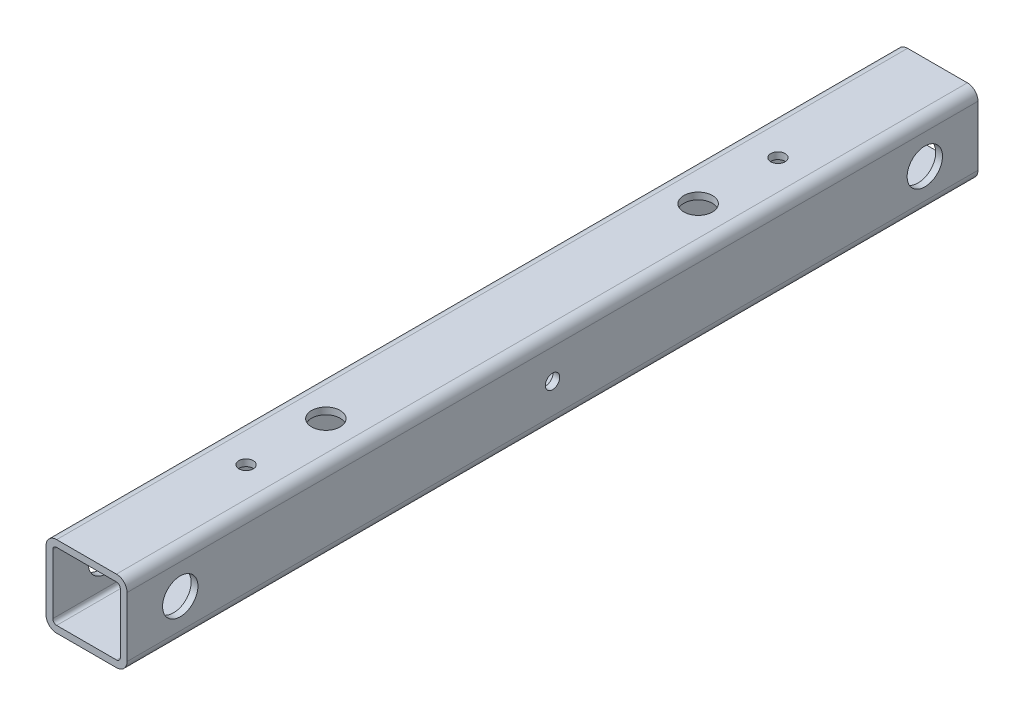
SolidWorks part; units mm, degrees
ref_plane "Front Plane" through (0, 0, 0) normal (0, 0, 1) x (1, 0, 0)
ref_plane "Top Plane" through (0, 0, 0) normal (0, 1, 0) x (1, 0, 0)
ref_plane "Right Plane" through (0, 0, 0) normal (1, 0, 0) x (0, 0, -1)
sketch "Sketch1" plane through (0, 0, 0) normal (0, 0, 1) x (1, 0, 0)
  line L6 (-14.05, 19.05) -> (14.05, 19.05)
  line L7 (19.05, 14.05) -> (19.05, -14.05)
  line L8 (-15.875, 14.05) -> (-15.875, -14.05)
  line L9 (-14.05, -15.875) -> (14.05, -15.875)
  line L10 (14.05, -19.05) -> (-14.05, -19.05)
  line L11 (-19.05, -14.05) -> (-19.05, 14.05)
  line L12 (0, 19.05) -> (0, -19.05) construction
  line L13 (-19.05, 0) -> (19.05, 0) construction
  line L14 (15.875, -14.05) -> (15.875, 14.05)
  line L15 (14.05, 15.875) -> (-14.05, 15.875)
  line L16 (0, 15.875) -> (0, -15.875) construction
  line L17 (-15.875, 0) -> (15.875, 0) construction
  arc A0 (14.05, 19.05) -> (19.05, 14.05) centre (14.05, 14.05) cw
  arc A1 (19.05, -14.05) -> (14.05, -19.05) centre (14.05, -14.05) cw
  arc A2 (-14.05, -19.05) -> (-19.05, -14.05) centre (-14.05, -14.05) cw
  arc A3 (-19.05, 14.05) -> (-14.05, 19.05) centre (-14.05, 14.05) cw
  arc A4 (-15.875, -14.05) -> (-14.05, -15.875) centre (-14.05, -14.05) ccw
  arc A5 (14.05, -15.875) -> (15.875, -14.05) centre (14.05, -14.05) ccw
  arc A6 (15.875, 14.05) -> (14.05, 15.875) centre (14.05, 14.05) ccw
  arc A7 (-14.05, 15.875) -> (-15.875, 14.05) centre (-14.05, 14.05) ccw
  point P40 (0, 0)
  dimension "D3" = 5
  dimension "D4" = 3.175
extrude "Boss-Extrude1" add sketch "Sketch1" along normal blind 400
sketch "Sketch2" plane through (0, 0, 0) normal (1, 0, 0) x (0, 0, -1)
  line L0 (-375, 0) -> (-25, 0) construction
  line L1 (20.955, 0) -> (-20.955, 0) construction
  line L2 (0, 20.955) -> (0, -20.955) construction
  circle A0 centre (-375, 0) radius 8.3125
  circle A1 centre (-25, 0) radius 8.3125
  dimension "D4" = 16.625
  dimension "D2" = 350
  dimension "D1" = 25
extrude "Cut-Extrude1" cut sketch "Sketch2" against normal through all both and the other way through all
sketch "Sketch3" plane through (0, 0, 0) normal (0, 1, 0) x (1, 0, 0)
  line L0 (0, -325) -> (0, -75) construction
  line L1 (0, -20.955) -> (0, 20.955) construction
  circle A0 centre (0, -325) radius 3.38
  circle A1 centre (0, -75) radius 3.38
  dimension "D4" = 6.76
  dimension "D2" = 250
  dimension "D3" = 75
extrude "Cut-Extrude2" cut sketch "Sketch3" along normal through all both and the other way through all
sketch "Centrepoint" plane through (0, 0, 0) normal (1, 0, 0) x (0, 0, -1)
  point P0 (-200, 0)
  dimension "D1" = 200
sketch "Sketch4" plane through (0, 0, 0) normal (1, 0, 0) x (0, 0, -1)
  line L0 (0, 20.955) -> (0, -20.955) construction
  line L1 (20.955, 0) -> (-20.955, 0) construction
  circle A0 centre (-200, 0) radius 3.38
  dimension "D1" = 6.76
  dimension "D2" = 200
extrude "Cut-Extrude3" cut sketch "Sketch4" against normal through all both and the other way through all
sketch "Sketch5" plane through (0, 0, 0) normal (1, 0, 0) x (0, 0, -1)
  line L0 (-188.1262, 8.4524) -> (-151.8738, -8.4524) construction
  line L1 (20.955, 0) -> (-20.955, 0) construction
  line L2 (0, 20.955) -> (0, -20.955) construction
  circle A0 centre (-188.1262, 8.4524) radius 3.38
  circle A1 centre (-151.8738, -8.4524) radius 3.38
  point P4 (-170, 0)
  dimension "D1" = 6.76
  dimension "D2" = 25
  dimension "D3" = 40
  dimension "D4" = 170
extrude "Cut-Extrude4" [suppressed] cut sketch "Sketch5" against normal through all both and the other way through all
sketch "Sketch6" plane through (0, 0, 0) normal (0, 1, 0) x (1, 0, 0)
  line L0 (0, -112.5) -> (0, -287.5) construction
  line L1 (0, -20.955) -> (0, 20.955) construction
  circle A0 centre (0, -112.5) radius 6.725
  circle A1 centre (0, -287.5) radius 6.725
  point P4 (0, -200)
  dimension "D1" = 13.45
  dimension "D2" = 175
  dimension "D3" = 200
extrude "Broom Mounting Holes" cut sketch "Sketch6" against normal through all both and the other way through all
equation "\"shovelHoleDiameter\"= 5in / 8 + 0.75"
equation "\"D4@Sketch2\"=\"shovelHoleDiameter\""
equation "\"mountHoleDiameter\"= 6.76mm"
equation "\"D4@Sketch3\"=\"mountHoleDiameter\""
equation "\"limitSwitchHoleDiameter\"= 6.76mm"
equation "\"D1@Sketch4\"=\"limitSwitchHoleDiameter\""
equation "\"bracketWidth\"= 400mm"
equation "\"mountingHoleDistance\"= 250mm"
equation "\"shovelHoleDistance\"= 350mm"
equation "\"D2@Sketch2\"=\"shovelHoleDistance\""
equation "\"D2@Sketch3\"=\"mountingHoleDistance\""
equation "\"D3@Sketch3\"=(\"bracketWidth\"-\"mountingHoleDistance\")/2"
equation "\"D2@Sketch4\"=\"bracketWidth\"/2"
equation "\"D1@Sketch5\"=\"mountHoleDiameter\""
equation "\"D4@Sketch5\"=\"bracketWidth\"/2 -30"
equation "\"D1@Sketch6\"=\"broomMountHolesDiameter\""
equation "\"D3@Sketch6\"=\"bracketWidth\"/2"
equation "\"broomMountHolesDiameter\"= 1in / 2 + 0.75mm"
